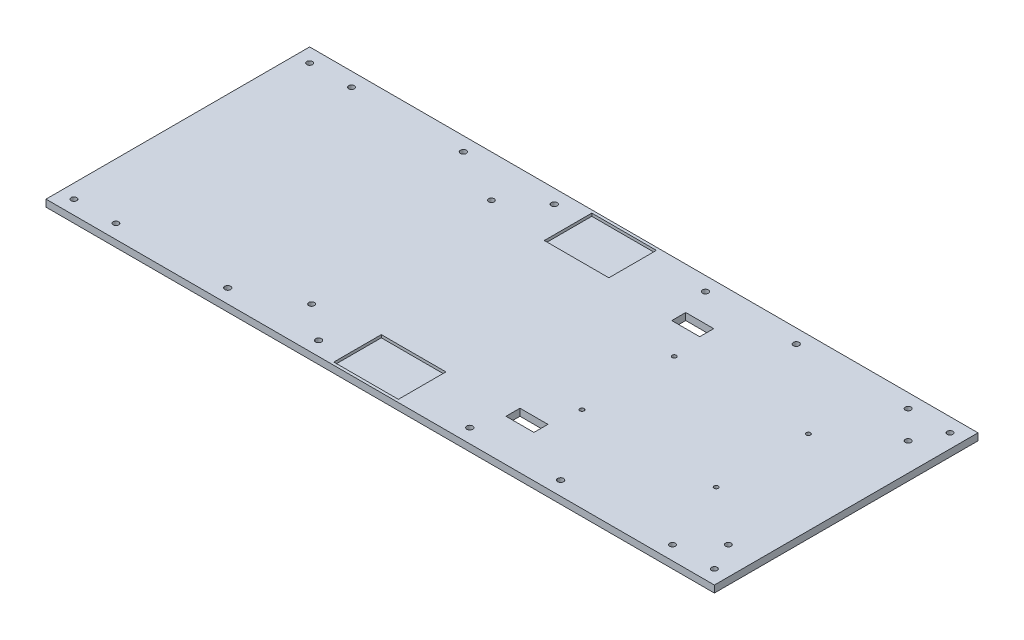
SolidWorks part; units mm, degrees
material "PMMA"
ref_plane "Plan de face" through (0, 0, 0) normal (0, 0, 1) x (1, 0, 0)
ref_plane "Plan de dessus" through (0, 0, 0) normal (0, 1, 0) x (1, 0, 0)
ref_plane "Plan de droite" through (0, 0, 0) normal (1, 0, 0) x (0, 0, -1)
sketch "Esquisse1" plane through (0, 0, 0) normal (0, 1, 0) x (1, 0, 0)
  line L0 (-72.9175, 47.0853) -> (405.2361, 47.0853)
  line L1 (-72.9175, 141.3821) -> (405.2361, 141.3821)
  line L2 (-72.9175, 141.3821) -> (-72.9175, -47.2116)
  line L3 (-72.9175, -47.2116) -> (405.2361, -47.2116)
  line L4 (405.2361, 141.3821) -> (405.2361, -47.2116)
  line L5 (-72.9175, -47.2116) -> (-62.9175, -47.2116)
  line L6 (-72.9175, -47.2116) -> (-72.9175, -37.2116)
  line L7 (-72.9175, -37.2116) -> (-62.9175, -37.2116)
  line L8 (-62.9175, -47.2116) -> (-62.9175, -37.2116)
  line L9 (-72.9175, 141.3821) -> (-62.9175, 141.3821)
  line L10 (-72.9175, 141.3821) -> (-72.9175, 131.3821)
  line L11 (-72.9175, 131.3821) -> (-62.9175, 131.3821)
  line L12 (-62.9175, 141.3821) -> (-62.9175, 131.3821)
  line L13 (405.2361, 141.3821) -> (395.2361, 141.3821)
  line L14 (405.2361, 141.3821) -> (405.2361, 131.3821)
  line L15 (405.2361, 131.3821) -> (395.2361, 131.3821)
  line L16 (395.2361, 141.3821) -> (395.2361, 131.3821)
  line L17 (405.2361, -47.2116) -> (395.2361, -47.2116)
  line L18 (405.2361, -47.2116) -> (405.2361, -37.2116)
  line L19 (405.2361, -37.2116) -> (395.2361, -37.2116)
  line L20 (395.2361, -47.2116) -> (395.2361, -37.2116)
  line L21 (166.1593, 141.3821) -> (166.1593, -47.2116)
  line L22 (-62.9175, 131.3821) -> (-32.9175, 131.3821)
  line L23 (166.1593, 47.0853) -> (200.1593, 47.0853)
  line L24 (166.1593, 47.0853) -> (166.1593, 56.9161)
  line L25 (166.1593, 56.9161) -> (200.1593, 56.9161)
  line L26 (200.1593, 47.0853) -> (200.1593, 56.9161)
  line L27 (166.1593, 56.9161) -> (132.1593, 56.9161)
  line L28 (166.1593, 56.9161) -> (166.1593, 47.0853)
  line L29 (166.1593, 47.0853) -> (132.1593, 47.0853)
  line L30 (132.1593, 56.9161) -> (132.1593, 47.0853)
  line L31 (-62.9175, -37.2116) -> (-32.9175, -37.2116)
  line L32 (395.2361, -37.2116) -> (365.2361, -37.2116)
  line L33 (395.2361, 131.3821) -> (365.2361, 131.3821)
  line L34 (166.1593, -47.2116) -> (246.1593, -47.2116)
  line L35 (132.1593, 47.0853) -> (200.1593, 47.0853)
  line L36 (132.1593, 47.0853) -> (132.1593, 39.6053)
  line L37 (132.1593, 39.6053) -> (200.1593, 39.6053)
  line L38 (200.1593, 47.0853) -> (200.1593, 39.6053)
  line L39 (132.1593, 56.9161) -> (200.1593, 56.9161)
  line L40 (132.1593, 56.9161) -> (132.1593, 102.9161)
  line L41 (132.1593, 102.9161) -> (200.1593, 102.9161)
  line L42 (200.1593, 56.9161) -> (200.1593, 102.9161)
  line L43 (132.1593, 39.6053) -> (200.1593, 39.6053)
  line L44 (132.1593, 39.6053) -> (132.1593, -6.3947)
  line L45 (132.1593, -6.3947) -> (200.1593, -6.3947)
  line L46 (200.1593, 39.6053) -> (200.1593, -6.3947)
  line L47 (166.1593, 141.3821) -> (246.1593, 141.3821)
  line L48 (246.1593, 141.3821) -> (246.1593, 111.3821)
  line L49 (246.1593, -47.2116) -> (246.1593, -17.2116)
  line L50 (246.1593, -17.2116) -> (226.1593, -17.2116)
  line L51 (226.1593, -17.2116) -> (226.1593, -7.2116)
  line L52 (226.1593, -7.2116) -> (246.1593, -7.2116)
  line L53 (246.1593, -7.2116) -> (246.1593, -17.2116)
  line L54 (246.1593, 111.3821) -> (226.1593, 111.3821)
  line L55 (226.1593, 111.3821) -> (226.1593, 101.3821)
  line L56 (226.1593, 101.3821) -> (246.1593, 101.3821)
  line L57 (246.1593, 101.3821) -> (246.1593, 111.3821)
  circle A0 centre (-62.9175, 131.3821) radius 2
  circle A1 centre (-62.9175, -37.2116) radius 2
  circle A2 centre (395.2361, -37.2116) radius 2
  circle A3 centre (395.2361, 131.3821) radius 2
  circle A4 centre (-32.9175, -37.2116) radius 2
  circle A5 centre (-32.9175, 131.3821) radius 2
  circle A6 centre (365.2361, 131.3821) radius 2
  circle A7 centre (365.2361, -37.2116) radius 2
extrude "Boss.-Extru.4" add sketch "Esquisse1" along normal blind 5
sketch "Esquisse2" plane through (0, 5, 0) normal (0, 1, 0) x (1, 0, 0)
  line L0 (-72.9175, -47.2116) -> (166.1593, -47.2116)
  line L1 (-72.9175, -47.2116) -> (405.2361, -47.2116) construction
  line L2 (166.1593, -47.2116) -> (166.1593, 141.3821)
  line L3 (-72.9175, 141.3821) -> (405.2361, 141.3821) construction
  line L4 (166.1593, -47.2116) -> (177.1593, -47.2116)
  line L5 (177.1593, -47.2116) -> (177.1593, 141.3821)
  line L6 (166.1593, 141.3821) -> (166.1593, 139.3821)
  line L7 (166.1593, 139.3821) -> (177.1593, 139.3821)
  line L8 (177.1593, -47.2116) -> (177.1593, -45.2116)
  line L9 (177.1593, -45.2116) -> (166.1593, -45.2116)
  line L10 (177.1593, -45.2116) -> (130.9593, -45.2116)
  line L11 (130.9593, -45.2116) -> (130.9593, 141.3821)
  line L12 (166.1593, 139.3821) -> (130.9593, 139.3821)
  line L13 (130.9593, -45.2116) -> (130.9593, -11.2116)
  line L14 (130.9593, -11.2116) -> (177.1593, -11.2116)
  line L15 (177.1593, 139.3821) -> (177.1593, 105.3821)
  line L16 (177.1593, 105.3821) -> (130.9593, 105.3821)
extrude "Enlèv. mat.-Extru.1" cut sketch "Esquisse2" against normal blind 2 contours L16 L2 L12 L11 | L16 L5 L7 L2 | L14 L11 L10 L2 | L14 L2 L9 L5
sketch "Esquisse3" plane through (0, 0, 0) normal (0, -1, 0) x (1, 0, 0)
  line L0 (405.2361, 47.2116) -> (385.2361, 47.2116)
  line L1 (385.2361, 47.2116) -> (385.2361, 17.2116)
  line L2 (405.2361, -141.3821) -> (385.2361, -141.3821)
  line L3 (385.2361, -141.3821) -> (385.2361, -111.3821)
  line L4 (-72.9175, 47.2116) -> (-72.9175, 17.2116)
  line L5 (-72.9175, 17.2116) -> (87.0825, 17.2116)
  line L6 (87.0825, 17.2116) -> (87.0825, 47.2116)
  line L7 (385.2361, 17.2116) -> (405.2361, 17.2116)
  line L8 (405.2361, -47.0853) -> (345.2361, -47.0853)
  line L9 (385.2361, -111.3821) -> (405.2361, -111.3821)
  line L10 (-72.9175, -141.3821) -> (-72.9175, -111.3821)
  line L11 (-72.9175, -111.3821) -> (87.0825, -111.3821)
  line L12 (87.0825, -111.3821) -> (87.0825, -141.3821)
  line L13 (345.2361, -47.0853) -> (345.2361, -14.0853)
  line L14 (345.2361, -47.0853) -> (345.2361, -80.0853)
  line L15 (345.2361, -80.0853) -> (249.2361, -80.0853)
  line L16 (249.2361, -80.0853) -> (249.2361, -14.0853)
  line L17 (249.2361, -14.0853) -> (345.2361, -14.0853)
  circle A0 centre (87.0825, -111.3821) radius 2
  circle A1 centre (87.0825, 17.2116) radius 2
  circle A2 centre (385.2361, -111.3821) radius 2
  circle A3 centre (385.2361, 17.2116) radius 2
  circle A4 centre (345.2361, -80.0853) radius 1.5
  circle A5 centre (249.2361, -80.0853) radius 1.5
  circle A6 centre (249.2361, -14.0853) radius 1.5
  circle A7 centre (345.2361, -14.0853) radius 1.5
extrude "Enlèv. mat.-Extru.2" cut sketch "Esquisse3" against normal blind 5 contours L9 A2 L3 | L3 A2 L9 | L1 A3 L7 | L7 A3 L1 | L15 A4 L14 | L14 A4 L15 | L13 A7 L17 | L17 A7 L13 | L16 A6 L17 | L17 A6 L16 | L16 A5 L15 | L15 A5 L16 | L6 A1 L5 | L5 A1 L6 | A0
sketch "Esquisse4" plane through (0, 0, 0) normal (0, -1, 0) x (1, 0, 0)
  line L0 (-72.9175, 47.2116) -> (-72.9175, 27.2116)
  line L1 (-72.9175, -141.3821) -> (-72.9175, 47.2116) construction
  line L2 (-72.9175, -141.3821) -> (-72.9175, -121.3821)
  line L3 (-72.9175, 27.2116) -> (-22.9175, 27.2116)
  line L4 (-22.9175, 27.2116) -> (-22.9175, 47.2116)
  line L5 (-72.9175, 47.2116) -> (405.2361, 47.2116) construction
  line L6 (-72.9175, -121.3821) -> (-22.9175, -121.3821)
  line L7 (-22.9175, -121.3821) -> (-22.9175, -141.3821)
  line L8 (-72.9175, -141.3821) -> (405.2361, -141.3821) construction
sketch "Esquisse5" plane through (0, 5, 0) normal (0, 1, 0) x (1, 0, 0)
  line L0 (365.2361, -37.2116) -> (285.2361, -37.2116)
  line L1 (365.2361, 131.3821) -> (285.2361, 131.3821)
  line L2 (-32.9175, 131.3821) -> (47.0825, 131.3821)
  line L3 (-32.9175, -37.2116) -> (47.0825, -37.2116)
  line L4 (47.0825, 131.3821) -> (47.0825, -37.2116)
  line L5 (285.2361, 131.3821) -> (285.2361, -37.2116)
  line L6 (285.2361, 131.3821) -> (220.2361, 131.3821)
  line L7 (285.2361, -37.2116) -> (220.2361, -37.2116)
  line L8 (47.0825, 131.3821) -> (112.0825, 131.3821)
  line L9 (47.0825, -37.2116) -> (112.0825, -37.2116)
  circle A0 centre (285.2361, 131.3821) radius 2.1
  circle A1 centre (285.2361, -37.2116) radius 2.1
  circle A2 centre (47.0825, 131.3821) radius 2.1
  circle A3 centre (47.0825, -37.2116) radius 2.1
  circle A4 centre (220.2361, 131.3821) radius 2.1
  circle A5 centre (220.2361, -37.2116) radius 2.1
  circle A6 centre (112.0825, 131.3821) radius 2.1
  circle A7 centre (112.0825, -37.2116) radius 2.1
  dimension "D1" = 80
  dimension "D5" = 80
  dimension "D2" = 80
  dimension "D3" = 80
  dimension "D4" = 80
  dimension "D6" = 65
  dimension "D7" = 65
  dimension "D8" = 65
  dimension "D9" = 65
extrude "Enlèv. mat.-Extru.3" cut sketch "Esquisse5" against normal blind 10 contours A0 | A1 | A4 | A5 | A6 | A2 | A7 | A3
